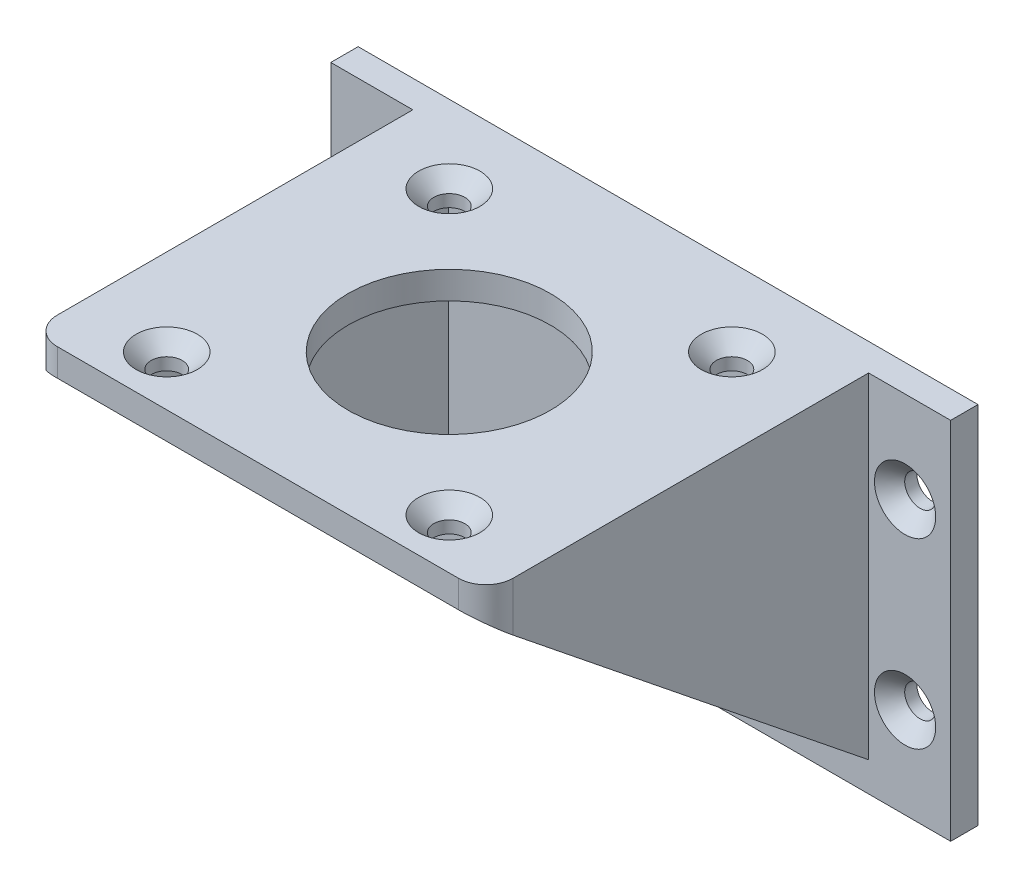
SolidWorks part; units mm, degrees
ref_plane "Front Plane" through (0, 0, 0) normal (0, 0, 1) x (1, 0, 0)
ref_plane "Top Plane" through (0, 0, 0) normal (0, 1, 0) x (1, 0, 0)
ref_plane "Right Plane" through (0, 0, 0) normal (1, 0, 0) x (0, 0, -1)
sketch "Sketch1" plane through (0, 0, 0) normal (0, 0, 1) x (1, 0, 0)
  line L1 (-34, 0) -> (34, 0)
  line L2 (-34, 0) -> (-34, -40)
  line L3 (-34, -40) -> (34, -40)
  line L4 (34, 0) -> (34, -40)
  point P4 (0, 0)
  dimension "D1" = 68
  dimension "D2" = 40
extrude "Boss-Extrude1" add sketch "Sketch1" along normal blind 3
sketch "Sketch3" plane through (0, 0, 0) normal (0, 1, 0) x (1, 0, 0)
  line L0 (34, -3) -> (-34, -3) construction
  line L1 (-25, -3) -> (25, -3)
  line L2 (-25, -3) -> (-25, -45)
  line L3 (-25, -45) -> (25, -45)
  line L4 (25, -3) -> (25, -45)
  point P6 (0, -3)
  dimension "D1" = 50
  dimension "D2" = 42
extrude "Boss-Extrude2" add sketch "Sketch3" against normal blind 3
sketch "Sketch4" plane through (0, 0, 0) normal (0, 1, 0) x (1, 0, 0)
  circle A3 centre (0, -24) radius 11.1
  circle A4 centre (0, -24) radius 11.1
  dimension "D1" = 0.1
extrude "Cut-Extrude1" cut sketch "Sketch4" against normal up to next
sketch "Sketch5" plane through (0, 0, 0) normal (0, 1, 0) x (1, 0, 0)
  point P0 (-15.5, -8.5)
  point P1 (15.5, -8.5)
  point P2 (-15.5, -39.5)
  point P3 (15.5, -39.5)
hole_wizard "CSK for M3 SFHCS1" positions "Sketch5" profile "Sketch6" countersink size "M3" standard "ANSI Metric" end condition up to next
sketch "Sketch6" plane through (-15.5, 0, 8.5) normal (1, 0, 0) x (0, 0, 1)
  line L0 (0, 0) -> (0, 3)
  line L1 (0, 3) -> (1.7, 3)
  line L2 (1.7, 3) -> (1.7, 1.66)
  line L3 (1.7, 1.66) -> (3.36, 0)
  line L5 (3.36, 0) -> (0, 0)
  line L6 (-1.7, 1.66) -> (-3.36, 0) construction
  line L11 (0, -6.35) -> (0, 107.95) construction
  dimension "Thru Hole Dia." = 3.4
  dimension "Thru Hole Depth" = 3
  dimension "Near C'Sink Dia." = 6.72
  dimension "Near C'Sink Angle" = 90
sketch "Sketch7" plane through (-25, 0, 0) normal (-1, 0, 0) x (0, 0, 1)
  line L0 (45, -3) -> (3, -36.75)
  line L1 (3, -36.75) -> (3, -3)
  line L2 (3, -3) -> (45, -3)
extrude "Boss-Extrude3" add sketch "Sketch7" against normal up to surface (50 mm away) up to face at (25, -1.5, 24)
sketch "Sketch9" plane through (0, -40, 0) normal (0, -1, 0) x (1, 0, 0)
  line L0 (25, 3) -> (-25, 3) construction
  line L1 (-21.1, 45) -> (21.1, 45)
  line L2 (-21.1, 45) -> (-21.1, 3)
  line L3 (-21.1, 3) -> (21.1, 3)
  line L4 (21.1, 45) -> (21.1, 3)
  line L5 (-21.1, 45) -> (21.1, 3) construction
  line L6 (-21.1, 3) -> (21.1, 45) construction
  line L7 (-21, 6.993) -> (-21, 41.007) construction
  point P0 (0, 24)
  dimension "D1" = 0.1
extrude "Cut-Extrude2" cut sketch "Sketch9" against normal up to vertex (37 mm away)
fillet "Fillet1" radius 3 2 edges at (25, -1.5, 45) (-25, -1.5, 45)
sketch "Sketch10" plane through (0, 0, 3) normal (0, 0, 1) x (1, 0, 0)
  line L0 (-34, 0) -> (-34, -40) construction
  line L1 (-29, -30) -> (29, -30) construction
  line L2 (-29, -30) -> (-29, -10) construction
  line L3 (-29, -10) -> (29, -10) construction
  line L4 (29, -30) -> (29, -10) construction
  line L5 (34, -40) -> (34, 0) construction
  line L6 (29, -20) -> (34, -20) construction
  point P0 (-29, -30)
  point P1 (29, -10)
  point P2 (-29, -10)
  point P3 (29, -30)
  point P4 (0, -30)
  dimension "D1" = 5
  dimension "D2" = 20
hole_wizard "CSK for M3 SFHCS2" positions "Sketch10" profile "Sketch11" countersink size "M3" standard "ANSI Metric" end condition up to next
sketch "Sketch11" plane through (-29, -30, 3) normal (1, 0, 0) x (0, -1, 0)
  line L0 (0, 0) -> (0, 3)
  line L1 (0, 3) -> (1.7, 3)
  line L2 (1.7, 3) -> (1.7, 1.66)
  line L3 (1.7, 1.66) -> (3.36, 0)
  line L5 (3.36, 0) -> (0, 0)
  line L6 (-1.7, 1.66) -> (-3.36, 0) construction
  line L11 (0, -6.35) -> (0, 107.95) construction
  dimension "Thru Hole Dia." = 3.4
  dimension "Thru Hole Depth" = 3
  dimension "Near C'Sink Dia." = 6.72
  dimension "Near C'Sink Angle" = 90
